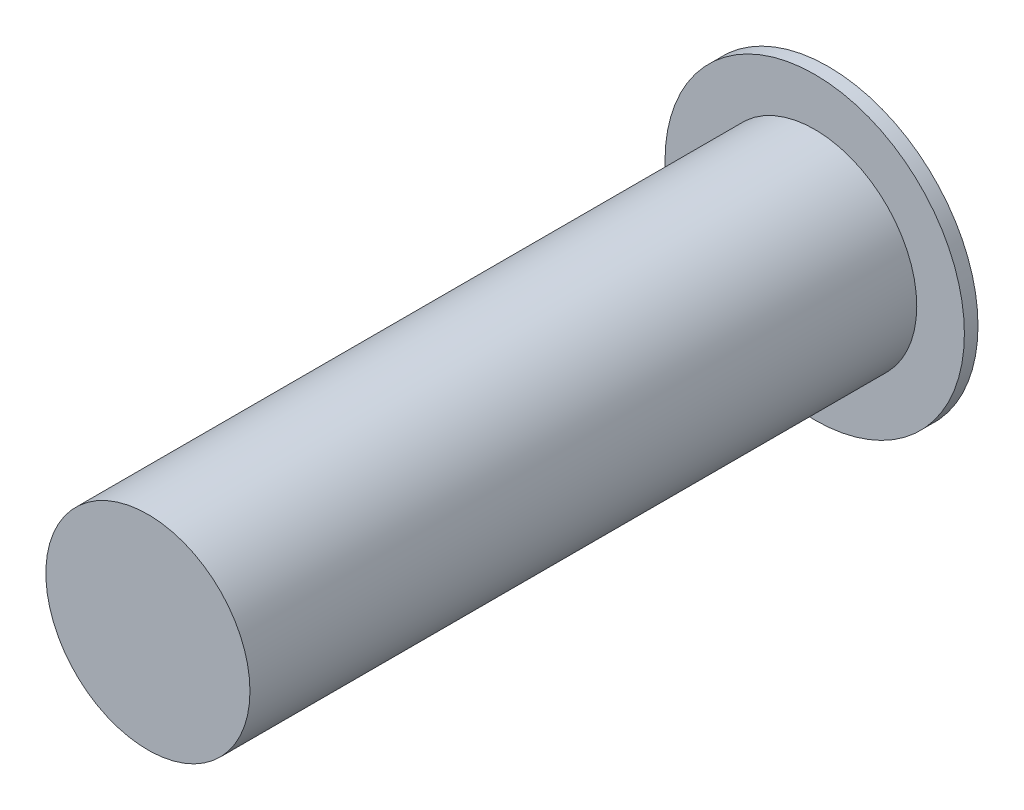
SolidWorks part; units mm, degrees
ref_plane "Front Plane" through (0, 0, 0) normal (0, 0, 1) x (1, 0, 0)
ref_plane "Top Plane" through (0, 0, 0) normal (0, 1, 0) x (1, 0, 0)
ref_plane "Right Plane" through (0, 0, 0) normal (1, 0, 0) x (0, 0, -1)
sketch "Sketch1" plane through (0, 0, 0) normal (0, 0, 1) x (1, 0, 0)
  circle A0 centre (0, 0) radius 22
  dimension "D1" = 44
extrude "Boss-Extrude1" add sketch "Sketch1" along normal blind 2 contours A0
sketch "Sketch2" plane through (0, 0, 0) normal (0, 0, 1) x (1, 0, 0)
  circle A0 centre (0, 0) radius 15
  dimension "D1" = 30
extrude "Boss-Extrude2" add sketch "Sketch2" along normal blind 100
sketch "Sketch3" plane through (0, 0, 0) normal (0, 1, 0) x (1, 0, 0)
  line L0 (-15, -2) -> (15, -2) construction
  line L1 (-6.8016, -10.3482) -> (6.8016, -10.3482)
  line L2 (-6.8016, -10.3482) -> (-6.8016, -4)
  line L3 (-6.8016, -4) -> (6.8016, -4)
  line L4 (6.8016, -10.3482) -> (6.8016, -4)
  line L5 (-6.8016, -10.3482) -> (6.8016, -4) construction
  line L6 (-6.8016, -4) -> (6.8016, -10.3482) construction
  point P0 (0, -7.1741)
  dimension "D1" = 2
